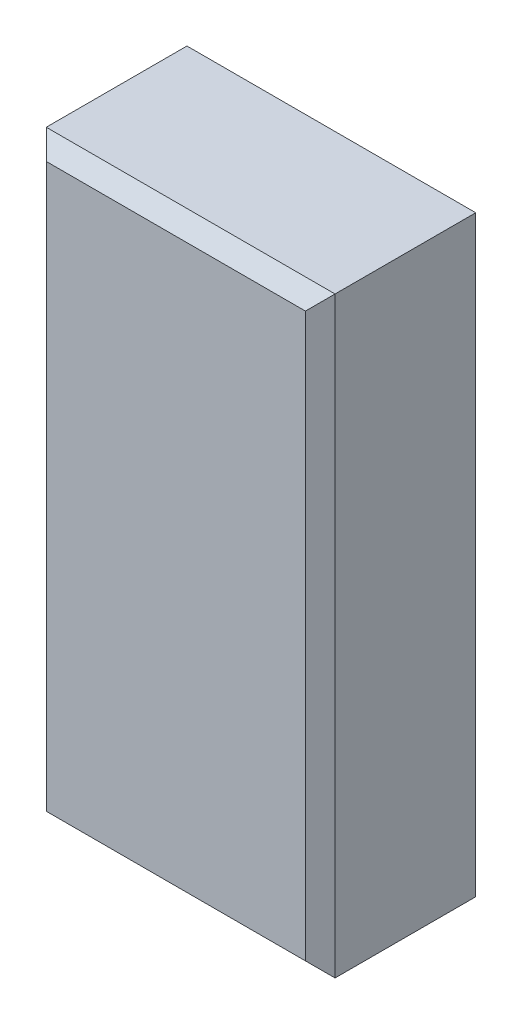
SolidWorks part; units mm, degrees
ref_plane "Front Plane" through (0, 0, 0) normal (0, 0, 1) x (1, 0, 0)
ref_plane "Top Plane" through (0, 0, 0) normal (0, 1, 0) x (1, 0, 0)
ref_plane "Right Plane" through (0, 0, 0) normal (1, 0, 0) x (0, 0, -1)
sketch "Sketch1" plane through (0, 0, 0) normal (0, 0, 1) x (1, 0, 0)
  line L1 (-9.75, 20) -> (9.75, 20)
  line L2 (-9.75, 20) -> (-9.75, -20)
  line L3 (-9.75, -20) -> (9.75, -20)
  line L4 (9.75, 20) -> (9.75, -20)
  line L5 (-9.75, 20) -> (9.75, -20) construction
  line L6 (-9.75, -20) -> (9.75, 20) construction
  point P0 (0, 0)
  dimension "D1" = 19.5
  dimension "D2" = 40
extrude "Boss-Extrude1" add sketch "Sketch1" along normal blind 11.5
chamfer "Chamfer1" distance 1 angle 45 8 edges at (0, 20, 0) (-9.75, 0, 0) (0, -20, 0) (9.75, 0, 0) (0, -20, 11.5) (-9.75, 0, 11.5) (0, 20, 11.5) (9.75, 0, 11.5)
equation "\"thiccnes\"=9.5"
equation "\"D1@Boss-Extrude1\"=\"thiccnes\""
